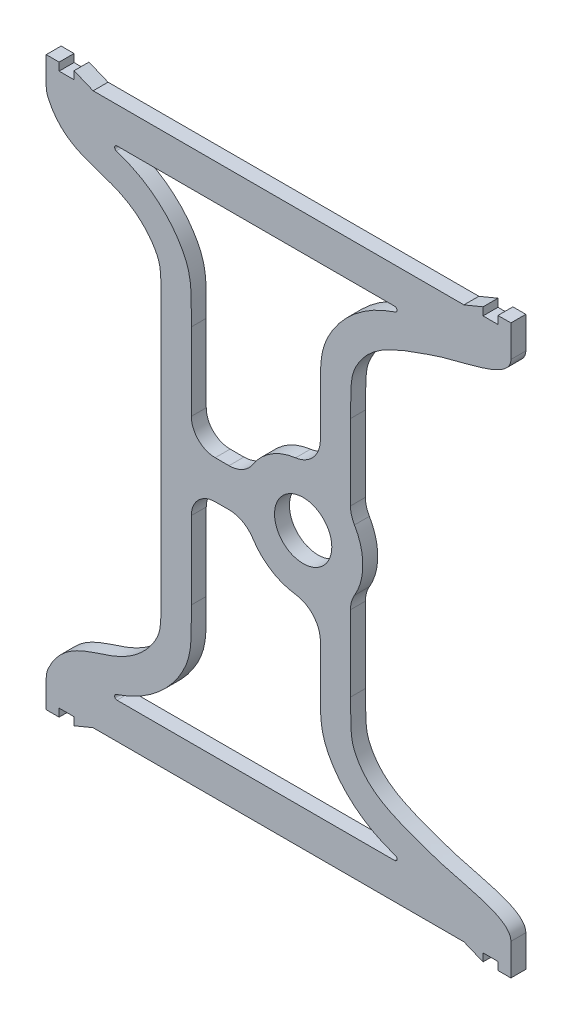
SolidWorks part; units mm, degrees
ref_plane "Front Plane" through (0, 0, 0) normal (0, 0, 1) x (1, 0, 0)
ref_plane "Top Plane" through (0, 0, 0) normal (0, 1, 0) x (1, 0, 0)
ref_plane "Right Plane" through (0, 0, 0) normal (1, 0, 0) x (0, 0, -1)
sketch "Sketch1" plane through (0, 0, 0) normal (0, 0, 1) x (1, 0, 0)
  line L0 (-41.684, 53.6194) -> (-41.684, 15.991) construction
  line L1 (-63.4451, 56.9953) -> (-61.4131, 56.1594)
  line L2 (-16.9595, 0) -> (-66.4086, 0) construction
  line L3 (-16.9595, 53.6194) -> (-16.9595, 56.9953)
  line L4 (-63.4451, 56.1594) -> (-63.4451, 56.9953)
  line L5 (-65.0326, 56.1594) -> (-65.0326, 56.9953)
  line L6 (-65.0326, 56.1594) -> (-63.4451, 56.1594)
  line L7 (-65.0326, 56.9953) -> (-66.4086, 56.9953)
  line L8 (-66.4086, 53.6194) -> (-66.4086, 56.9953)
  line L9 (-21.9549, 56.1594) -> (-61.4131, 56.1594)
  line L10 (-63.4451, -3.3759) -> (-61.4131, -2.54)
  line L11 (-19.9229, 56.1594) -> (-19.9229, 56.9953)
  line L12 (-16.9595, 53.6194) -> (-66.4086, 53.6194) construction
  line L13 (-18.3354, 56.1594) -> (-18.3354, 56.9953)
  line L14 (-18.3354, 56.1594) -> (-19.9229, 56.1594)
  line L15 (-41.684, 0) -> (-41.684, 37.6284) construction
  line L16 (-63.4451, -2.54) -> (-63.4451, -3.3759)
  line L17 (-65.0326, -2.54) -> (-63.4451, -2.54)
  line L18 (-54.1675, 13.9741) -> (-54.1675, 39.6453)
  line L19 (-19.9229, 56.9953) -> (-21.9549, 56.1594)
  line L20 (-65.0326, -2.54) -> (-65.0326, -3.3759)
  line L21 (-65.0326, -3.3759) -> (-66.4086, -3.3759)
  line L22 (-39.0652, 26.8097) -> (0, 26.8097) construction
  line L23 (-66.4086, 0) -> (-66.4086, -3.3759)
  line L24 (0, 18.0594) -> (0, 35.56) construction
  line L25 (-21.9549, -2.54) -> (-61.4131, -2.54)
  line L26 (-19.9229, 56.1594) -> (-21.9549, 56.1594) construction
  line L27 (-19.9229, -3.3759) -> (-21.9549, -2.54)
  line L28 (-19.9229, -2.54) -> (-19.9229, -3.3759)
  line L29 (-18.3354, -2.54) -> (-19.9229, -2.54)
  line L30 (-18.3354, -2.54) -> (-18.3354, -3.3759)
  line L31 (-18.3354, -3.3759) -> (-16.9595, -3.3759)
  line L32 (-16.9595, 0) -> (-16.9595, -3.3759)
  line L33 (-19.9229, -41.0126) -> (-20.6907, -38.9352)
  line L34 (-60.4202, 1.27) -> (-27.7757, 1.27)
  line L35 (-60.4202, 52.3494) -> (-27.7757, 52.3494)
  line L40 (-18.3354, 56.9953) -> (-16.9595, 56.9953)
  line L45 (-50.9642, 13.9953) -> (-50.9642, 22.2377)
  line L46 (-37.2317, 13.9953) -> (-37.2317, 17.5181)
  line L47 (-46.9548, 28.8417) -> (-48.4242, 28.8417)
  line L48 (-37.2317, 36.1013) -> (-37.2317, 39.6241)
  line L49 (-50.9642, 31.3817) -> (-50.9642, 39.6241)
  line L50 (-34.0284, 39.6453) -> (-34.0284, 31.5926)
  line L51 (-46.9548, 24.7777) -> (-48.4242, 24.7777)
  line L52 (-34.0284, 22.0268) -> (-34.0284, 13.9741)
  line L53 (-49.6835, 24.7777) -> (-49.6835, 26.8097) construction
  line L54 (-49.6835, 26.8097) -> (-49.6835, 28.8417) construction
  line L57 (-18.3354, -42.5808) -> (-16.9595, -44.0195)
  circle A3 centre (-39.0652, 26.8097) radius 3.048 construction
  circle A4 centre (-39.0652, 26.8097) radius 3.048
  arc A8 (-33.6055, 23.5672) -> (-33.6055, 30.0522) centre (-39.0652, 26.8097) ccw
  arc A12 (-39.8673, 33.1088) -> (-44.4138, 30.2324) centre (-39.0652, 26.8097) ccw
  circle A13 centre (-39.0652, 26.8097) radius 6.35 construction
  arc A14 (-44.4138, 23.387) -> (-39.8673, 20.5106) centre (-39.0652, 26.8097) ccw
  arc A15 (-44.4138, 30.2324) -> (-46.9548, 28.8417) centre (-46.9548, 31.8584) cw
  arc A16 (-46.9548, 24.7777) -> (-44.4138, 23.387) centre (-46.9548, 21.761) cw
  arc A17 (-34.0284, 31.5926) -> (-33.6055, 30.0522) centre (-31.0117, 31.5926) ccw
  arc A18 (-33.6055, 23.5672) -> (-34.0284, 22.0268) centre (-31.0117, 22.0268) ccw
  arc A19 (-37.2317, 36.1013) -> (-39.8673, 33.1088) centre (-40.2483, 36.1013) cw
  arc A20 (-39.8673, 20.5106) -> (-37.2317, 17.5181) centre (-40.2483, 17.5181) cw
  arc A21 (-48.4242, 24.7777) -> (-50.9642, 22.2377) centre (-48.4242, 22.2377) ccw
  arc A22 (-48.4242, 28.8417) -> (-50.9642, 31.3817) centre (-48.4242, 31.3817) cw
  spline S0 degree 3 poles (-16.9595, 53.6194) (-16.9587, 51.7069) (-22.3477, 50.8733) (-27.9702, 48.9153) (-28.3324, 48.7786) (-32.04, 47.0588) (-34.0439, 44.0842) (-33.9777, 42.8412) (-34.0284, 39.6453) knots 0 0 0 0 0.161069 0.199423 0.36308 0.414818 0.696343 1 1 1 1
  spline S1 degree 3 poles (-66.4086, 53.6194) (-64.9241, 49.6484) (-61.0934, 49.4187) (-56.3573, 47.1016) (-54.0564, 44.0672) (-54.2181, 42.8337) (-54.1675, 39.6453) knots 0 0 0 0 0.364565 0.416182 0.697051 1 1 1 1
  spline S4 degree 3 poles (-50.9642, 39.6241) (-50.966, 39.8504) (-50.9687, 40.3216) (-50.9709, 41.1152) (-50.9734, 41.9664) (-50.9931, 42.8397) (-51.0597, 43.7066) (-51.2382, 44.6498) (-51.5668, 45.5684) (-51.9443, 46.3246) (-52.5939, 47.3938) (-53.4878, 48.4993) (-54.6631, 49.5708) (-55.6941, 50.3301) (-56.8646, 51.0169) (-58.2109, 51.6074) (-59.2182, 51.9452) (-59.9439, 52.1853) (-60.258, 52.2919) (-60.4202, 52.3494) knots 0.254794 0.254794 0.254794 0.254794 0.278081 0.301369 0.347944 0.39452 0.441095 0.487671 0.534246 0.580821 0.627397 0.720548 0.767123 0.813698 0.860274 0.906849 0.953425 0.976712 1 1 1 1
  spline S5 degree 3 poles (-27.7757, 52.3494) (-27.9379, 52.2919) (-28.2519, 52.1853) (-28.9777, 51.9452) (-29.985, 51.6074) (-31.3313, 51.0169) (-32.5017, 50.3301) (-33.5327, 49.5708) (-34.7081, 48.4993) (-35.6019, 47.3938) (-36.2515, 46.3246) (-36.629, 45.5684) (-36.9577, 44.6498) (-37.1361, 43.7066) (-37.2028, 42.8397) (-37.2225, 41.9664) (-37.2249, 41.1152) (-37.2271, 40.3216) (-37.2298, 39.8504) (-37.2317, 39.6241) knots 0.254794 0.254794 0.254794 0.254794 0.278081 0.301369 0.347944 0.39452 0.441095 0.487671 0.534246 0.627397 0.673972 0.720548 0.767123 0.813698 0.860274 0.906849 0.953425 0.976712 1 1 1 1
  spline S6 degree 3 poles (-27.7757, 1.27) (-27.9379, 1.3275) (-28.2519, 1.4341) (-28.9777, 1.6742) (-29.985, 2.012) (-31.3313, 2.6025) (-32.5017, 3.2893) (-33.5327, 4.0486) (-34.7081, 5.1201) (-35.6019, 6.2256) (-36.2515, 7.2948) (-36.629, 8.051) (-36.9577, 8.9696) (-37.1361, 9.9128) (-37.2028, 10.7797) (-37.2225, 11.653) (-37.2249, 12.5042) (-37.2271, 13.2978) (-37.2298, 13.769) (-37.2317, 13.9953) knots 0.254794 0.254794 0.254794 0.254794 0.278081 0.301369 0.347944 0.39452 0.441095 0.487671 0.534246 0.627397 0.673972 0.720548 0.767123 0.813698 0.860274 0.906849 0.953425 0.976712 1 1 1 1
  spline S7 degree 3 poles (-50.9642, 13.9953) (-50.966, 13.769) (-50.9687, 13.2978) (-50.9709, 12.5042) (-50.9734, 11.653) (-50.9931, 10.7797) (-51.0597, 9.9128) (-51.2382, 8.9696) (-51.5668, 8.051) (-51.9443, 7.2948) (-52.5939, 6.2256) (-53.4878, 5.1201) (-54.6631, 4.0486) (-55.6941, 3.2893) (-56.8646, 2.6025) (-58.2109, 2.012) (-59.2182, 1.6742) (-59.9439, 1.4341) (-60.258, 1.3275) (-60.4202, 1.27) knots 0.254794 0.254794 0.254794 0.254794 0.278081 0.301369 0.347944 0.39452 0.441095 0.487671 0.534246 0.580821 0.627397 0.720548 0.767123 0.813698 0.860274 0.906849 0.953425 0.976712 1 1 1 1
  spline S8 degree 3 poles (-66.4086, 0) (-64.9241, 3.971) (-61.0934, 4.2007) (-56.3573, 6.5178) (-54.0564, 9.5522) (-54.2181, 10.7857) (-54.1675, 13.9741) knots 0 0 0 0 0.364565 0.416182 0.697051 1 1 1 1
  spline S9 degree 3 poles (-16.9595, 0) (-16.9587, 1.9125) (-22.3477, 2.7461) (-27.9702, 4.7041) (-28.3324, 4.8408) (-32.04, 6.5606) (-34.0439, 9.5352) (-33.9777, 10.7782) (-34.0284, 13.9741) knots 0 0 0 0 0.161069 0.199423 0.36308 0.414818 0.696343 1 1 1 1
  point P100 (-32.7152, 26.8097)
  point P112 (-45.0813, 24.7777)
  point P119 (-37.2317, 32.8892)
  point P126 (-50.9642, 28.8417)
  dimension "D6" = 0.8359
  dimension "D7" = 2.54
  dimension "D13" = 3.302
  dimension "D14" = 4.064
  dimension "D15" = 3.0167
  dimension "D16" = 2.54
  dimension "D2" = 1.27
  dimension "D3" = 1.376
  dimension "D4" = 2.032
extrude "Boss-Extrude2" add sketch "Sketch1" along normal blind 1.5875
fillet "Fillet1" radius 0.254 4 edges at (-27.7757, 1.27, 0.7937) (-60.4202, 1.27, 0.7937) (-60.4202, 52.3494, 0.7937) (-27.7757, 52.3494, 0.7937)
fillet "Fillet2" radius 2.54 2 edges at (-66.4086, 0, 0.7937) (-66.4086, 53.6194, 0.7937)
